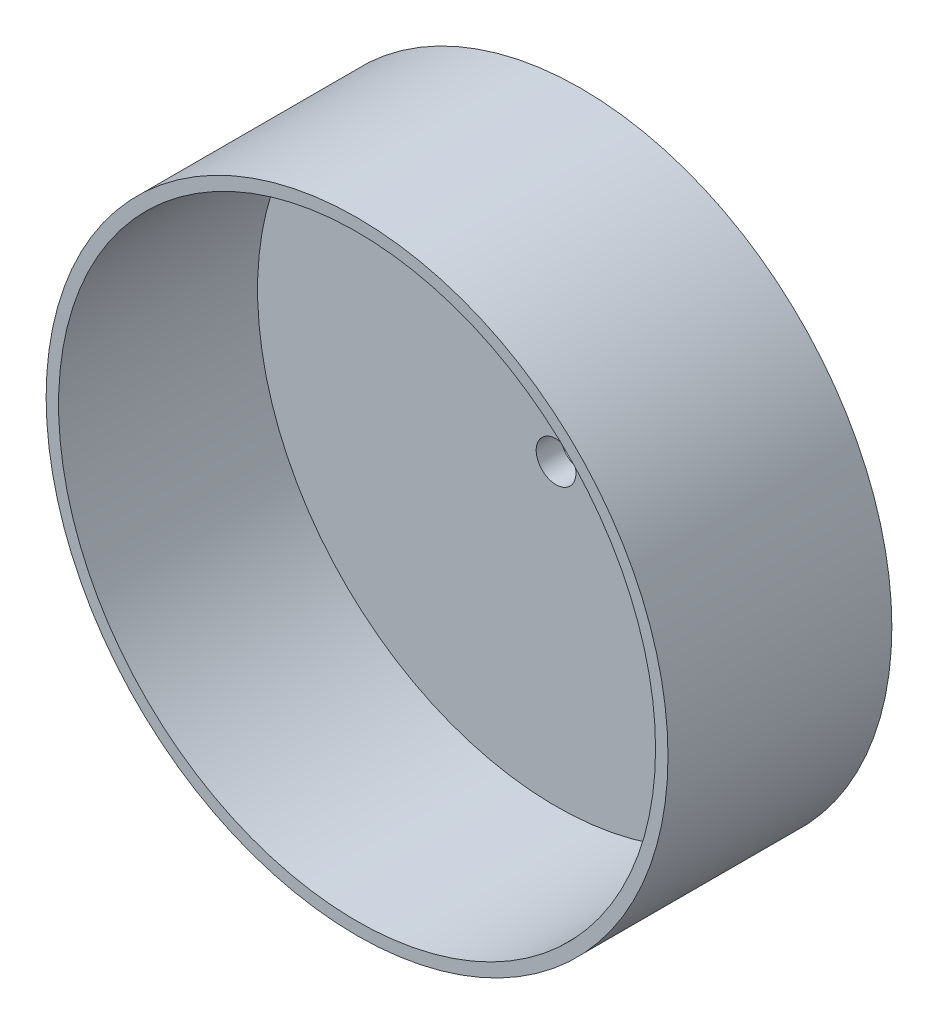
SolidWorks part; units mm, degrees
ref_plane "Front Plane" through (0, 0, 0) normal (0, 0, 1) x (1, 0, 0)
ref_plane "Top Plane" through (0, 0, 0) normal (0, 1, 0) x (1, 0, 0)
ref_plane "Right Plane" through (0, 0, 0) normal (1, 0, 0) x (0, 0, -1)
sketch "Sketch1" plane through (0, 0, 0) normal (0, 0, 1) x (1, 0, 0)
  circle A0 centre (0, 0) radius 62.5
  circle A1 centre (0, 0) radius 4
  dimension "D1" = 8
  dimension "D2" = 125
extrude "Boss-Extrude1" add sketch "Sketch1" along normal blind 45
sketch "Sketch2" plane through (0, 0, 45) normal (0, 0, 1) x (1, 0, 0)
  circle A0 centre (0, 0) radius 60
  dimension "D1" = 120
extrude "Cut-Extrude1" cut sketch "Sketch2" against normal blind 40
